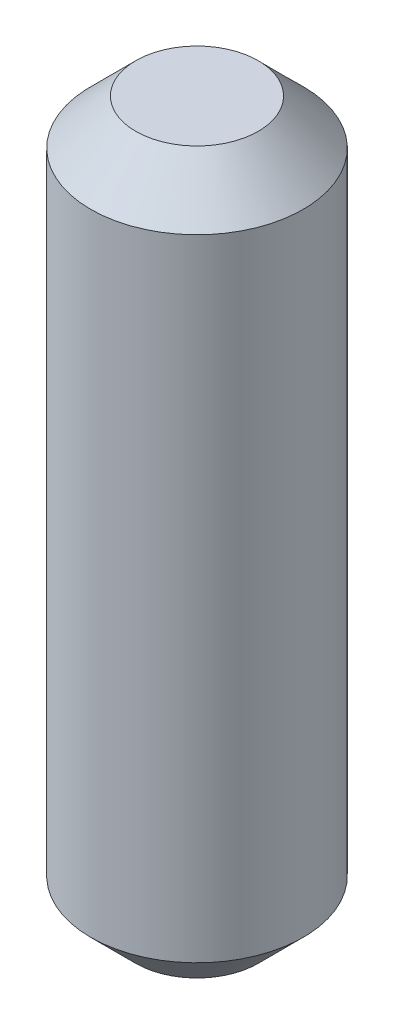
SolidWorks part; units mm, degrees
ref_plane "Front Plane" through (0, 0, 0) normal (0, 0, 1) x (1, 0, 0)
ref_plane "Top Plane" through (0, 0, 0) normal (0, 1, 0) x (1, 0, 0)
ref_plane "Right Plane" through (0, 0, 0) normal (1, 0, 0) x (0, 0, -1)
sketch "Sketch2" plane through (0, 0, 0) normal (0, 1, 0) x (1, 0, 0)
  circle A0 centre (0, 0) radius 2.9972
  dimension "D1" = 5.9944
extrude "Boss-Extrude1" add sketch "Sketch2" along normal blind 20.32
chamfer "Chamfer1" distance 1.27 angle 45 2 edges at (0, 20.32, 2.9972) (0, 0, 2.9972)
